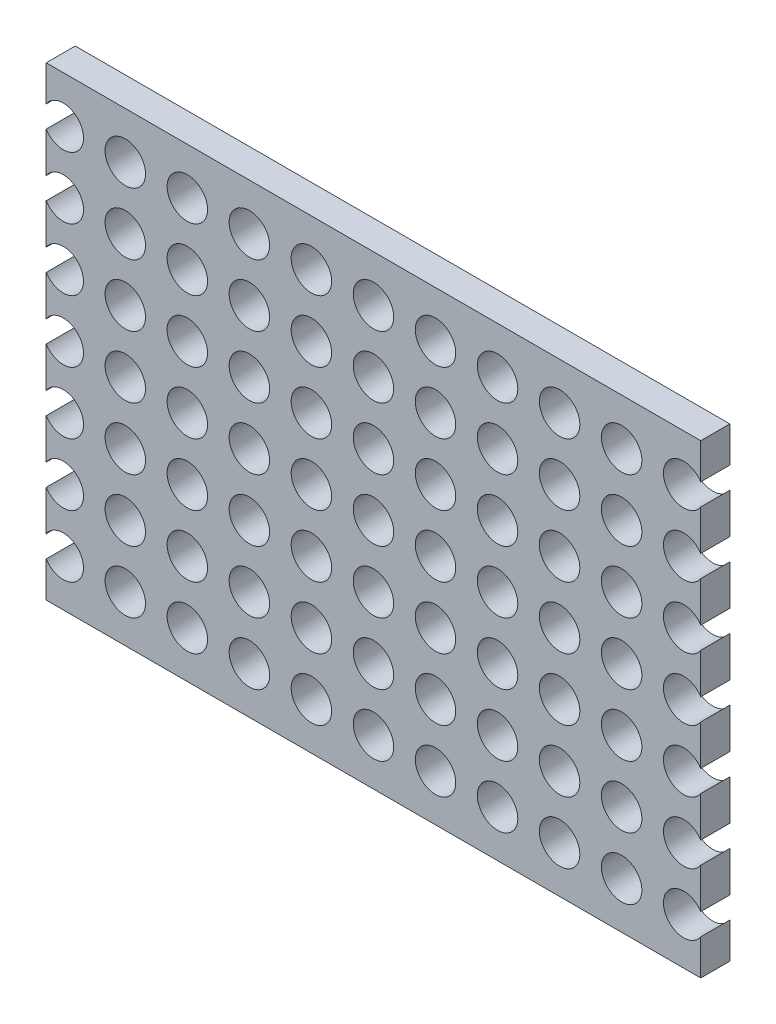
SolidWorks part; units mm, degrees
material "Nylon 6/10"
ref_plane "Front Plane" through (0, 0, 0) normal (0, 0, 1) x (1, 0, 0)
ref_plane "Top Plane" through (0, 0, 0) normal (0, 1, 0) x (1, 0, 0)
ref_plane "Right Plane" through (0, 0, 0) normal (1, 0, 0) x (0, 0, -1)
sketch "Sketch1" plane through (0, 0, 0) normal (0, 0, 1) x (1, 0, 0)
  line L1 (-53.594, -38.1) -> (53.594, -38.1)
  line L2 (-53.594, -38.1) -> (-53.594, 38.1)
  line L3 (-53.594, 38.1) -> (53.594, 38.1)
  line L4 (53.594, -38.1) -> (53.594, 38.1)
  line L5 (-53.594, -38.1) -> (53.594, 38.1) construction
  line L6 (-53.594, 38.1) -> (53.594, -38.1) construction
  point P0 (0, 0)
  dimension "D1" = 107.188
  dimension "D2" = 76.2
extrude "Extrude1" add sketch "Sketch1" along normal blind 4.7625
sketch "Sketch3" plane through (0, 0, 4.7625) normal (0, 0, 1) x (1, 0, 0)
  point P0 (0, 0)
hole_wizard "G (0.261) Diameter Hole1" positions "Sketch6" profile "Sketch5" hole size "G" standard "Ansi Inch"
sketch "Sketch6" plane through (0, 0, 4.7625) normal (0, 0, 1) x (1, 0, 0)
  point P2 (0, 0)
sketch "Sketch5" plane through (0, 0, 4.7625) normal (1, 0, 0) x (0, -1, 0)
  line L0 (0, 0) -> (0, 17.2317)
  line L1 (0, 17.2317) -> (3.3147, 15.24)
  line L2 (3.3147, 15.24) -> (3.3147, 0)
  line L5 (3.3147, 0) -> (0, 0)
  line L10 (0, 17.2317) -> (-3.3147, 15.24) construction
  line L11 (0, -6.35) -> (0, 107.95) construction
  dimension "Hole Dia." = 6.6294
  dimension "Hole Depth" = 15.24
  dimension "Drill Angle" = 118
pattern_linear "LPattern1" count 6 spacing 10.16 along (1, 0, 0) count 6 spacing 10.16 along (-1, 0, 0) of "G (0.261) Diameter Hole1"
pattern_linear "LPattern2" count 4 spacing 10.16 along (0, -1, 0) count 4 spacing 10.16 along (0, 1, 0) of "LPattern1", "G (0.261) Diameter Hole1"
